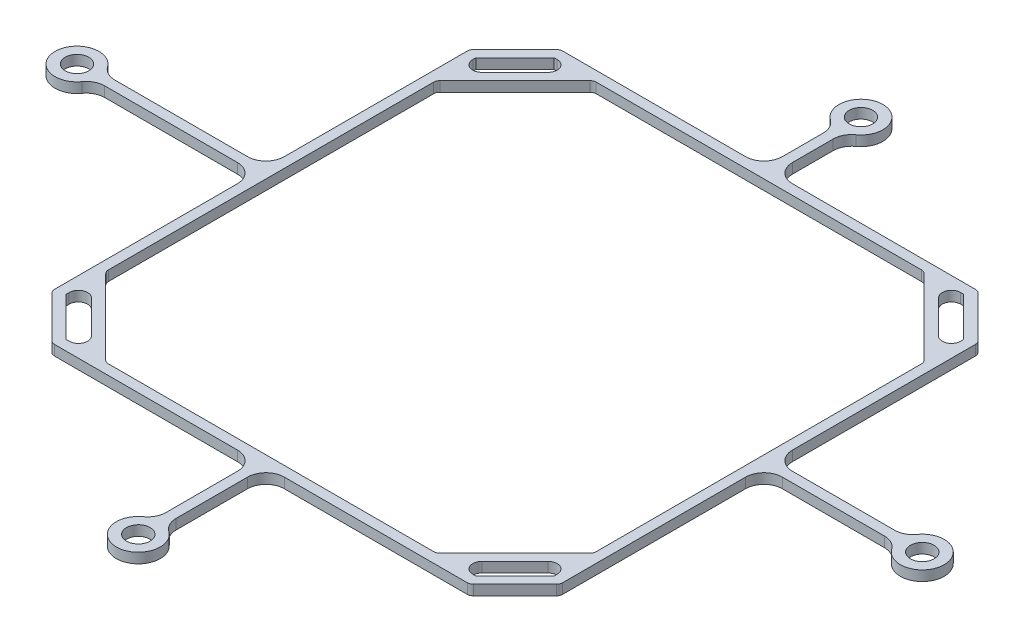
SolidWorks part; units mm, degrees
material "Strong and Flexible"
ref_plane "Front Plane" through (0, 0, 0) normal (0, 0, 1) x (1, 0, 0)
ref_plane "Top Plane" through (0, 0, 0) normal (0, 1, 0) x (1, 0, 0)
ref_plane "Right Plane" through (0, 0, 0) normal (1, 0, 0) x (0, 0, -1)
sketch "Sketch1" plane through (0, 0, 0) normal (0, 1, 0) x (1, 0, 0)
  line L0 (0, 0) -> (0, 56.4488) construction
  line L1 (0, 0) -> (-71.4488, 0) construction
  line L2 (-39.7988, 33.4083) -> (-33.4083, 39.7988)
  line L3 (-33.4083, -39.7988) -> (-29.2929, -39.7988)
  line L4 (-39.7988, -33.4083) -> (-39.7988, -29.2929)
  line L5 (-33.4083, 39.7988) -> (-29.2929, 39.7988)
  line L6 (39.7988, -33.4083) -> (39.7988, -29.2929)
  line L7 (-39.7988, -39.7988) -> (36.6035, 36.6035) construction
  line L8 (-36.6035, 36.6035) -> (39.7988, -39.7988) construction
  line L9 (33.4083, 39.7988) -> (39.7988, 33.4083)
  line L10 (39.7988, -33.4083) -> (33.4083, -39.7988)
  line L11 (-33.4083, -39.7988) -> (-39.7988, -33.4083)
  line L12 (-41.4488, 34.0917) -> (-34.0917, 41.4488)
  line L13 (34.0917, 41.4488) -> (0.825, 41.4488)
  line L14 (34.0917, 41.4488) -> (41.4488, 34.0917)
  line L15 (41.4488, -34.0917) -> (41.4488, -0.825)
  line L16 (41.4488, -34.0917) -> (34.0917, -41.4488)
  line L17 (-34.0917, -41.4488) -> (-0.825, -41.4488)
  line L18 (-34.0917, -41.4488) -> (-41.4488, -34.0917)
  line L19 (-41.4488, 34.0917) -> (-41.4488, 0.825)
  line L20 (-39.7988, 29.2929) -> (-29.2929, 39.7988)
  line L21 (-39.7988, 26.9594) -> (-26.9594, 39.7988)
  line L22 (29.2929, 39.7988) -> (39.7988, 29.2929)
  line L23 (26.9594, 39.7988) -> (39.7988, 26.9594)
  line L24 (39.7988, -29.2929) -> (29.2929, -39.7988)
  line L25 (39.7988, -26.9594) -> (26.9594, -39.7988)
  line L26 (-29.2929, -39.7988) -> (-39.7988, -29.2929)
  line L27 (-26.9594, -39.7988) -> (-39.7988, -26.9594)
  line L28 (-39.7988, 29.2929) -> (-39.7988, 33.4083)
  line L29 (-26.9594, 39.7988) -> (26.9594, 39.7988)
  line L30 (29.2929, 39.7988) -> (33.4083, 39.7988)
  line L31 (39.7988, 29.2929) -> (39.7988, 33.4083)
  line L32 (39.7988, -26.9594) -> (39.7988, 26.9594)
  line L33 (-39.7988, -26.9594) -> (-39.7988, 26.9594)
  line L34 (-26.9594, -39.7988) -> (26.9594, -39.7988)
  line L35 (29.2929, -39.7988) -> (33.4083, -39.7988)
  line L36 (62.9703, -0.825) -> (41.4488, -0.825)
  line L37 (0.825, 52.9703) -> (0.825, 41.4488)
  line L38 (-0.825, 52.9703) -> (-0.825, 41.4488)
  line L39 (62.9703, 0.825) -> (41.4488, 0.825)
  line L40 (-0.825, -57.9703) -> (-0.825, -41.4488)
  line L41 (0.825, -57.9703) -> (0.825, -41.4488)
  line L42 (-67.9703, 0.825) -> (-41.4488, 0.825)
  line L43 (-67.9703, -0.825) -> (-41.4488, -0.825)
  line L44 (0, 0) -> (0, -61.4488) construction
  line L45 (41.4488, 0.825) -> (41.4488, 34.0917)
  line L46 (-0.825, 41.4488) -> (-34.0917, 41.4488)
  line L47 (-41.4488, -0.825) -> (-41.4488, -34.0917)
  line L48 (0.825, -41.4488) -> (34.0917, -41.4488)
  arc A0 (0.825, 52.9703) -> (-0.825, 52.9703) centre (0, 56.4488) ccw
  circle A1 centre (0, 56.4488) radius 1.925
  circle A2 centre (66.4488, 0) radius 1.925
  arc A3 (62.9703, 0.825) -> (62.9703, -0.825) centre (66.4488, 0) cw
  arc A4 (-0.825, -57.9703) -> (0.825, -57.9703) centre (0, -61.4488) ccw
  circle A5 centre (0, -61.4488) radius 1.925
  arc A6 (-67.9703, 0.825) -> (-67.9703, -0.825) centre (-71.4488, 0) ccw
  circle A7 centre (-71.4488, 0) radius 1.925
  point P19 (0, 0)
  point P20 (0, 0)
  point P33 (0, 0)
  point P46 (0, 0)
  point P74 (0, 0)
  dimension "D10" = 3.85
  dimension "D11" = 1.65
  dimension "D15" = 1.65
  dimension "D16" = 3.85
  dimension "D20" = 3.85
  dimension "D21" = 1.65
  dimension "D27" = 3.85
  dimension "D29" = 1.65
  dimension "D1" = 1.65
  dimension "D2" = 79.5976
  dimension "D3" = 9.0376
  dimension "D5" = 1.65
  dimension "D6" = 4
  dimension "D7" = 2.91
  dimension "D8" = 1.65
  dimension "D12" = 0.825
  dimension "D13" = 0.825
  dimension "D14" = 15
  dimension "D17" = 30
  dimension "D18" = 0.825
  dimension "D19" = 0.825
  dimension "D22" = 0.825
  dimension "D23" = 0.825
  dimension "D24" = 20
  dimension "D25" = 12.8394
  dimension "D26" = 25
  dimension "D4" = 4
  dimension "D9" = 4
extrude "Boss-Extrude1" add sketch "Sketch1" along normal blind 1.65
fillet "Fillet4" radius 3 16 edges at (0.825, 0.825, -41.4488) (0.825, 0.825, -52.9703) (-0.825, 0.825, -52.9703) (-0.825, 0.825, -41.4488) (62.9703, 0.825, -0.825) (62.9703, 0.825, 0.825) (41.4488, 0.825, -0.825) (41.4488, 0.825, 0.825) (0.825, 0.825, 57.9703) (-0.825, 0.825, 57.9703) (-0.825, 0.825, 41.4488) (0.825, 0.825, 41.4488) (-41.4488, 0.825, 0.825) (-41.4488, 0.825, -0.825) (-67.9703, 0.825, 0.825) (-67.9703, 0.825, -0.825)
fillet "Fillet3" radius 1.5 8 edges at (29.2929, 0.825, 39.7988) (39.7988, 0.825, 29.2929) (-29.2929, 0.825, 39.7988) (-39.7988, 0.825, 29.2929) (-39.7988, 0.825, -29.2929) (-29.2929, 0.825, -39.7988) (39.7988, 0.825, -29.2929) (29.2929, 0.825, -39.7988)
fillet "Fillet5" radius 1 16 edges at (-26.9594, 0.825, 39.7988) (-39.7988, 0.825, 26.9594) (-41.4488, 0.825, 34.0917) (-34.0917, 0.825, 41.4488) (-39.7988, 0.825, -26.9594) (-26.9594, 0.825, -39.7988) (-41.4488, 0.825, -34.0917) (-34.0917, 0.825, -41.4488) (41.4488, 0.825, -34.0917) (34.0917, 0.825, -41.4488) (26.9594, 0.825, -39.7988) (39.7988, 0.825, -26.9594) (34.0917, 0.825, 41.4488) (41.4488, 0.825, 34.0917) (39.7988, 0.825, 26.9594) (26.9594, 0.825, 39.7988)
